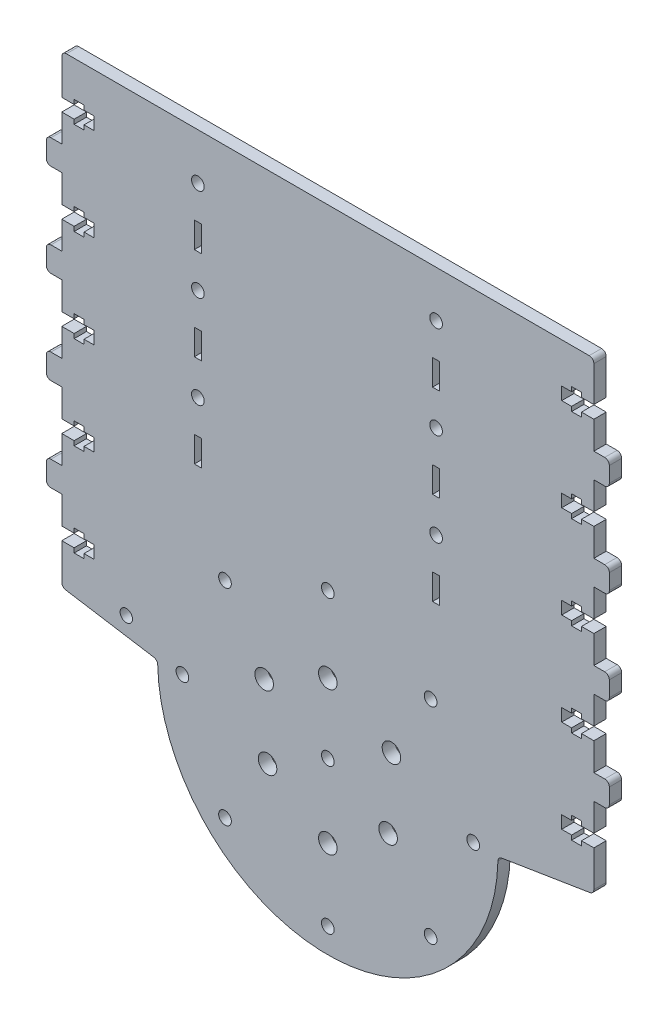
SolidWorks part; units mm, degrees
ref_plane "前视基准面" through (0, 0, 0) normal (0, 0, 1) x (1, 0, 0)
ref_plane "上视基准面" through (0, 0, 0) normal (0, 1, 0) x (1, 0, 0)
ref_plane "右视基准面" through (0, 0, 0) normal (1, 0, 0) x (0, 0, -1)
sketch "草图1" plane through (0, 0, 0) normal (0, 0, 1) x (1, 0, 0)
  line L9 (143, 45.95) -> (147, 45.95)
  line L10 (147, 45.95) -> (147, 44.5)
  line L11 (147, 44.5) -> (150.2, 44.5)
  line L12 (150.2, 44.5) -> (150.2, 45.95)
  line L13 (150.2, 45.95) -> (153.4, 45.95)
  line L14 (153.4, 45.95) -> (153.4, 50.05)
  line L23 (143, 48) -> (141.6922, 48) construction
  line L24 (143, 45.95) -> (143, 50.05) construction
  line L25 (150.2, 51.5) -> (150.2, 50.05)
  line L26 (147, 50.05) -> (147, 51.5)
  line L27 (150.2, 50.05) -> (153.4, 50.05)
  line L28 (147, 51.5) -> (150.2, 51.5)
  line L29 (143, 50.05) -> (147, 50.05)
  line L31 (143, 29) -> (138, 29)
  line L32 (138, 29) -> (138, 37)
  line L33 (138, 37) -> (143, 37)
  line L34 (143, 37) -> (143, 45.95)
  line L35 (138, 33) -> (143, 33) construction
  line L43 (143, 119) -> (143, 123)
  line L44 (229, -79) -> (229, -87) construction
  line L45 (143, 20.05) -> (143, 15.95) construction
  line L69 (143, -97) -> (311, -97) construction
  line L70 (143, 18) -> (141.6922, 18) construction
  line L71 (143, 15.95) -> (147, 15.95)
  line L72 (147, 15.95) -> (147, 14.5)
  line L73 (147, 14.5) -> (150.2, 14.5)
  line L98 (150.2, 14.5) -> (150.2, 15.95)
  line L123 (150.2, 15.95) -> (153.4, 15.95)
  line L124 (150.2, 21.5) -> (150.2, 20.05)
  line L125 (147, 20.05) -> (147, 21.5)
  line L126 (150.2, 20.05) -> (153.4, 20.05)
  line L127 (147, 21.5) -> (150.2, 21.5)
  line L128 (143, 20.05) -> (147, 20.05)
  line L129 (143, 7) -> (143, 15.95)
  line L130 (143, 15.95) -> (147, 15.95)
  line L131 (147, 14.5) -> (150.2, 14.5)
  line L132 (143, 15.95) -> (147, 15.95)
  line L133 (147, 15.95) -> (147, 14.5)
  line L134 (147, 14.5) -> (150.2, 14.5)
  line L135 (150.2, 14.5) -> (150.2, 15.95)
  line L136 (150.2, 15.95) -> (153.4, 15.95)
  line L137 (150.2, 21.5) -> (150.2, 20.05)
  line L138 (147, 20.05) -> (147, 21.5)
  line L139 (150.2, 20.05) -> (153.4, 20.05)
  line L140 (147, 21.5) -> (150.2, 21.5)
  line L141 (143, 20.05) -> (147, 20.05)
  line L142 (150.2, 15.95) -> (153.4, 15.95)
  line L143 (147, 15.95) -> (147, 14.5)
  line L144 (150.2, 14.5) -> (150.2, 15.95)
  line L145 (150.2, 20.05) -> (153.4, 20.05)
  line L146 (150.2, 21.5) -> (150.2, 20.05)
  line L147 (147, 21.5) -> (150.2, 21.5)
  line L148 (147, 20.05) -> (147, 21.5)
  line L149 (143, 20.05) -> (147, 20.05)
  line L150 (143, 45.95) -> (147, 45.95)
  line L151 (147, 45.95) -> (147, 44.5)
  line L152 (147, 44.5) -> (150.2, 44.5)
  line L153 (150.2, 44.5) -> (150.2, 45.95)
  line L154 (150.2, 45.95) -> (153.4, 45.95)
  line L155 (150.2, 51.5) -> (150.2, 50.05)
  line L156 (147, 50.05) -> (147, 51.5)
  line L157 (150.2, 50.05) -> (153.4, 50.05)
  line L158 (143, 45.95) -> (147, 45.95)
  line L159 (147, 44.5) -> (150.2, 44.5)
  line L160 (150.2, 45.95) -> (153.4, 45.95)
  line L161 (147, 45.95) -> (147, 44.5)
  line L162 (150.2, 44.5) -> (150.2, 45.95)
  line L163 (150.2, 50.05) -> (153.4, 50.05)
  line L164 (150.2, 51.5) -> (150.2, 50.05)
  line L165 (147, 51.5) -> (150.2, 51.5)
  line L166 (147, 50.05) -> (147, 51.5)
  line L167 (143, 50.05) -> (147, 50.05)
  line L168 (147, 51.5) -> (150.2, 51.5)
  line L169 (143, 50.05) -> (147, 50.05)
  line L170 (143, 29) -> (143, 20.05)
  line L171 (143, 15.95) -> (147, 15.95)
  line L172 (147, 14.5) -> (150.2, 14.5)
  line L173 (150.2, 15.95) -> (153.4, 15.95)
  line L174 (147, 15.95) -> (147, 14.5)
  line L175 (150.2, 14.5) -> (150.2, 15.95)
  line L177 (153.4, 20.05) -> (153.4, 15.95)
  line L178 (150.2, 20.05) -> (153.4, 20.05)
  line L179 (150.2, 21.5) -> (150.2, 20.05)
  line L180 (147, 21.5) -> (150.2, 21.5)
  line L181 (147, 20.05) -> (147, 21.5)
  line L182 (143, 20.05) -> (147, 20.05)
  line L183 (138, 3) -> (143, 3) construction
  line L184 (138, -1) -> (143, -1)
  line L185 (138, 7) -> (138, -1)
  line L186 (143, 7) -> (138, 7)
  line L187 (138, 93) -> (143, 93) construction
  line L188 (143, 78) -> (141.6922, 78) construction
  line L189 (272.15, 28.85) -> (269.85, 37.15) construction
  line L190 (138, 63) -> (143, 63) construction
  line L191 (143, 89) -> (138, 89)
  line L192 (138, 89) -> (138, 97)
  line L193 (138, 97) -> (143, 97)
  line L194 (143, 75.95) -> (147, 75.95)
  line L195 (147, 75.95) -> (147, 74.5)
  line L196 (147, 74.5) -> (150.2, 74.5)
  line L197 (150.2, 74.5) -> (150.2, 75.95)
  line L198 (150.2, 75.95) -> (153.4, 75.95)
  line L199 (143, 59) -> (143, 50.05)
  line L200 (138, 59) -> (143, 59)
  line L201 (153.4, 75.95) -> (153.4, 80.05)
  line L202 (150.2, 81.5) -> (150.2, 80.05)
  line L203 (143, 45.95) -> (147, 45.95)
  line L204 (147, 44.5) -> (150.2, 44.5)
  line L205 (150.2, 45.95) -> (153.4, 45.95)
  line L206 (147, 45.95) -> (147, 44.5)
  line L207 (150.2, 44.5) -> (150.2, 45.95)
  line L208 (150.2, 50.05) -> (153.4, 50.05)
  line L209 (150.2, 51.5) -> (150.2, 50.05)
  line L210 (147, 51.5) -> (150.2, 51.5)
  line L211 (147, 50.05) -> (147, 51.5)
  line L212 (143, 50.05) -> (147, 50.05)
  line L213 (272.15, 37.15) -> (269.85, 28.85) construction
  line L214 (147, 80.05) -> (147, 81.5)
  line L215 (150.2, 80.05) -> (153.4, 80.05)
  line L216 (147, 81.5) -> (150.2, 81.5)
  line L217 (143, 80.05) -> (147, 80.05)
  line L218 (143, 67) -> (143, 75.95)
  line L219 (143, 75.95) -> (147, 75.95)
  line L220 (147, 75.95) -> (147, 74.5)
  line L221 (147, 74.5) -> (150.2, 74.5)
  line L222 (150.2, 74.5) -> (150.2, 75.95)
  line L223 (150.2, 75.95) -> (153.4, 75.95)
  line L224 (150.2, 81.5) -> (150.2, 80.05)
  line L225 (147, 80.05) -> (147, 81.5)
  line L227 (271, 48) -> (271, 33) construction
  line L228 (272.15, 58.85) -> (269.85, 67.15) construction
  line L229 (272.15, 67.15) -> (269.85, 58.85) construction
  line L230 (150.2, 80.05) -> (153.4, 80.05)
  line L231 (143, 75.95) -> (147, 75.95)
  line L232 (147, 74.5) -> (150.2, 74.5)
  line L233 (150.2, 75.95) -> (153.4, 75.95)
  line L234 (147, 75.95) -> (147, 74.5)
  line L235 (150.2, 74.5) -> (150.2, 75.95)
  line L253 (150.2, 80.05) -> (153.4, 80.05)
  line L254 (150.2, 81.5) -> (150.2, 80.05)
  line L255 (143, -27) -> (143, -97) construction
  line L256 (147, 81.5) -> (150.2, 81.5)
  line L257 (147, 80.05) -> (147, 81.5)
  line L258 (143, 80.05) -> (147, 80.05)
  line L259 (147, 81.5) -> (150.2, 81.5)
  line L260 (143, 80.05) -> (147, 80.05)
  line L261 (143, 89) -> (143, 80.05)
  line L262 (143, 75.95) -> (147, 75.95)
  line L263 (147, 74.5) -> (150.2, 74.5)
  line L264 (150.2, 75.95) -> (153.4, 75.95)
  line L265 (147, 75.95) -> (147, 74.5)
  line L267 (150.2, 74.5) -> (150.2, 75.95)
  line L269 (150.2, 80.05) -> (153.4, 80.05)
  line L270 (150.2, 81.5) -> (150.2, 80.05)
  line L272 (147, 81.5) -> (150.2, 81.5)
  line L273 (147, 80.05) -> (147, 81.5)
  line L274 (143, 80.05) -> (147, 80.05)
  line L275 (138, 59) -> (143, 59)
  line L277 (138, 67) -> (138, 59)
  line L278 (143, 67) -> (138, 67)
  line L279 (143, 110.05) -> (143, 105.95) construction
  line L280 (143, 108) -> (141.6922, 108) construction
  line L281 (272.15, 88.85) -> (269.85, 97.15) construction
  line L282 (143, 105.95) -> (147, 105.95)
  line L283 (147, 105.95) -> (147, 104.5)
  line L284 (147, 104.5) -> (150.2, 104.5)
  line L285 (150.2, 104.5) -> (150.2, 105.95)
  line L286 (150.2, 105.95) -> (153.4, 105.95)
  line L287 (150.2, 111.5) -> (150.2, 110.05)
  line L288 (147, 110.05) -> (147, 111.5)
  line L289 (150.2, 110.05) -> (153.4, 110.05)
  line L290 (147, 111.5) -> (150.2, 111.5)
  line L291 (143, 110.05) -> (147, 110.05)
  line L292 (143, 97) -> (143, 105.95)
  line L293 (143, 105.95) -> (147, 105.95)
  line L294 (147, 104.5) -> (150.2, 104.5)
  line L296 (143, 105.95) -> (147, 105.95)
  line L300 (147, 105.95) -> (147, 104.5)
  line L301 (147, 104.5) -> (150.2, 104.5)
  line L302 (150.2, 104.5) -> (150.2, 105.95)
  line L303 (150.2, 105.95) -> (153.4, 105.95)
  line L304 (150.2, 111.5) -> (150.2, 110.05)
  line L305 (147, 110.05) -> (147, 111.5)
  line L306 (150.2, 110.05) -> (153.4, 110.05)
  line L307 (147, 111.5) -> (150.2, 111.5)
  line L308 (143, 110.05) -> (147, 110.05)
  line L309 (150.2, 105.95) -> (153.4, 105.95)
  line L310 (147, 105.95) -> (147, 104.5)
  line L312 (150.2, 104.5) -> (150.2, 105.95)
  line L314 (150.2, 110.05) -> (153.4, 110.05)
  line L315 (150.2, 111.5) -> (150.2, 110.05)
  line L317 (147, 111.5) -> (150.2, 111.5)
  line L320 (147, 110.05) -> (147, 111.5)
  line L321 (143, 110.05) -> (147, 110.05)
  line L322 (143, 119) -> (143, 110.05)
  line L323 (143, 105.95) -> (147, 105.95)
  line L324 (147, 104.5) -> (150.2, 104.5)
  line L325 (150.2, 105.95) -> (153.4, 105.95)
  line L326 (147, 105.95) -> (147, 104.5)
  line L327 (150.2, 104.5) -> (150.2, 105.95)
  line L328 (153.4, 110.05) -> (153.4, 105.95)
  line L329 (150.2, 110.05) -> (153.4, 110.05)
  line L330 (150.2, 111.5) -> (150.2, 110.05)
  line L331 (147, 111.5) -> (150.2, 111.5)
  line L332 (147, 110.05) -> (147, 111.5)
  line L333 (143, 110.05) -> (147, 110.05)
  line L334 (143, -14.05) -> (147, -14.05)
  line L335 (272.15, 97.15) -> (269.85, 88.85) construction
  line L336 (271, 108) -> (271, 48) construction
  line L337 (269.85, 37.15) -> (269.85, 28.85) construction
  line L338 (272.15, 28.85) -> (269.85, 28.85) construction
  line L339 (272.15, 37.15) -> (272.15, 28.85) construction
  line L340 (272.15, 37.15) -> (269.85, 37.15) construction
  line L341 (269.85, 67.15) -> (269.85, 58.85) construction
  line L342 (272.15, 58.85) -> (269.85, 58.85) construction
  line L343 (272.15, 67.15) -> (272.15, 58.85) construction
  line L344 (272.15, 67.15) -> (269.85, 67.15) construction
  line L345 (269.85, 97.15) -> (269.85, 88.85) construction
  line L346 (272.15, 88.85) -> (269.85, 88.85) construction
  line L347 (272.15, 97.15) -> (272.15, 88.85) construction
  line L348 (272.15, 97.15) -> (269.85, 97.15) construction
  line L349 (307.8, 110.05) -> (304.6, 110.05)
  line L350 (304.6, 110.05) -> (304.6, 105.95)
  line L352 (307.8, 105.95) -> (304.6, 105.95)
  line L353 (307.8, 110.05) -> (304.6, 110.05)
  line L355 (307.8, 105.95) -> (304.6, 105.95)
  line L357 (307.8, 110.05) -> (304.6, 110.05)
  line L358 (307.8, 105.95) -> (304.6, 105.95)
  line L359 (307.8, 110.05) -> (304.6, 110.05)
  line L360 (307.8, 105.95) -> (304.6, 105.95)
  line L361 (307.8, 80.05) -> (304.6, 80.05)
  line L362 (307.8, 75.95) -> (304.6, 75.95)
  line L363 (307.8, 80.05) -> (304.6, 80.05)
  line L364 (307.8, 75.95) -> (304.6, 75.95)
  line L365 (307.8, 80.05) -> (304.6, 80.05)
  line L367 (307.8, 75.95) -> (304.6, 75.95)
  line L369 (187, 108) -> (187, 48) construction
  line L370 (185.85, 97.15) -> (188.15, 97.15)
  line L371 (185.85, 97.15) -> (185.85, 88.85)
  line L372 (185.85, 88.85) -> (188.15, 88.85)
  line L373 (188.15, 97.15) -> (188.15, 88.85)
  line L374 (185.85, 97.15) -> (188.15, 88.85) construction
  line L375 (185.85, 88.85) -> (188.15, 97.15) construction
  line L387 (307.8, 80.05) -> (304.6, 80.05)
  line L389 (307.8, 50.05) -> (304.6, 50.05)
  line L391 (307.8, 45.95) -> (304.6, 45.95)
  line L392 (304.6, 75.95) -> (304.6, 80.05)
  line L420 (307.8, 75.95) -> (304.6, 75.95)
  line L421 (229, -32) -> (245.7973, -32) construction
  line L422 (229, -32) -> (253.7224, -46.2735) construction
  line L423 (185.85, 67.15) -> (188.15, 67.15)
  line L424 (185.85, 67.15) -> (185.85, 58.85)
  line L425 (185.85, 58.85) -> (188.15, 58.85)
  line L426 (188.15, 67.15) -> (188.15, 58.85)
  line L427 (185.85, 67.15) -> (188.15, 58.85) construction
  line L432 (185.85, 58.85) -> (188.15, 67.15) construction
  line L433 (307.8, 20.05) -> (304.6, 20.05)
  line L443 (187, 48) -> (187, 33) construction
  line L444 (304.6, 20.05) -> (304.6, 15.95)
  line L445 (185.85, 37.15) -> (188.15, 37.15)
  line L446 (185.85, 37.15) -> (185.85, 28.85)
  line L447 (185.85, 28.85) -> (188.15, 28.85)
  line L448 (188.15, 37.15) -> (188.15, 28.85)
  line L449 (185.85, 37.15) -> (188.15, 28.85) construction
  line L450 (185.85, 28.85) -> (188.15, 37.15) construction
  line L451 (307.8, 15.95) -> (304.6, 15.95)
  line L452 (307.8, 50.05) -> (304.6, 50.05)
  line L453 (307.8, 45.95) -> (304.6, 45.95)
  line L454 (307.8, 50.05) -> (304.6, 50.05)
  line L455 (307.8, 45.95) -> (304.6, 45.95)
  line L456 (307.8, 20.05) -> (304.6, 20.05)
  line L457 (307.8, 15.95) -> (304.6, 15.95)
  line L458 (307.8, 20.05) -> (304.6, 20.05)
  line L459 (307.8, 15.95) -> (304.6, 15.95)
  line L460 (307.8, 20.05) -> (304.6, 20.05)
  line L461 (307.8, 15.95) -> (304.6, 15.95)
  line L462 (307.8, 50.05) -> (304.6, 50.05)
  line L463 (304.6, 45.95) -> (304.6, 50.05)
  line L464 (307.8, 45.95) -> (304.6, 45.95)
  line L465 (315, 108) -> (316.3078, 108) construction
  line L466 (315, 110.05) -> (315, 105.95) construction
  line L467 (320, 63) -> (315, 63) construction
  line L468 (315, 78) -> (316.3078, 78) construction
  line L469 (320, 93) -> (315, 93) construction
  line L470 (320, 3) -> (315, 3) construction
  line L471 (315, 18) -> (316.3078, 18) construction
  line L472 (315, 20.05) -> (315, 15.95) construction
  line L473 (320, 33) -> (315, 33) construction
  line L474 (315, 45.95) -> (315, 50.05) construction
  line L475 (315, 48) -> (316.3078, 48) construction
  line L476 (315, -14.05) -> (315, -27)
  line L477 (315, 110.05) -> (311, 110.05)
  line L478 (311, 110.05) -> (311, 111.5)
  line L479 (311, 111.5) -> (307.8, 111.5)
  line L480 (307.8, 111.5) -> (307.8, 110.05)
  line L481 (307.8, 104.5) -> (307.8, 105.95)
  line L482 (311, 105.95) -> (311, 104.5)
  line L483 (311, 104.5) -> (307.8, 104.5)
  line L484 (315, 105.95) -> (311, 105.95)
  line L485 (315, 119) -> (315, 110.05)
  line L486 (315, 110.05) -> (311, 110.05)
  line L487 (311, 110.05) -> (311, 111.5)
  line L488 (311, 111.5) -> (307.8, 111.5)
  line L489 (307.8, 111.5) -> (307.8, 110.05)
  line L490 (307.8, 104.5) -> (307.8, 105.95)
  line L491 (311, 105.95) -> (311, 104.5)
  line L492 (315, 110.05) -> (311, 110.05)
  line L493 (311, 111.5) -> (307.8, 111.5)
  line L494 (311, 110.05) -> (311, 111.5)
  line L495 (307.8, 111.5) -> (307.8, 110.05)
  line L496 (307.8, 104.5) -> (307.8, 105.95)
  line L497 (311, 104.5) -> (307.8, 104.5)
  line L498 (311, 105.95) -> (311, 104.5)
  line L499 (315, 105.95) -> (311, 105.95)
  line L500 (311, 104.5) -> (307.8, 104.5)
  line L501 (315, 105.95) -> (311, 105.95)
  line L502 (315, 97) -> (315, 105.95)
  line L503 (315, 110.05) -> (311, 110.05)
  line L504 (311, 111.5) -> (307.8, 111.5)
  line L505 (311, 110.05) -> (311, 111.5)
  line L506 (307.8, 111.5) -> (307.8, 110.05)
  line L507 (307.8, 104.5) -> (307.8, 105.95)
  line L508 (311, 104.5) -> (307.8, 104.5)
  line L509 (311, 105.95) -> (311, 104.5)
  line L510 (315, 105.95) -> (311, 105.95)
  line L511 (315, 67) -> (320, 67)
  line L512 (320, 67) -> (320, 59)
  line L513 (320, 59) -> (315, 59)
  line L514 (315, 80.05) -> (311, 80.05)
  line L515 (311, 80.05) -> (311, 81.5)
  line L516 (311, 81.5) -> (307.8, 81.5)
  line L517 (307.8, 81.5) -> (307.8, 80.05)
  line L518 (307.8, 74.5) -> (307.8, 75.95)
  line L519 (311, 75.95) -> (311, 74.5)
  line L520 (311, 74.5) -> (307.8, 74.5)
  line L521 (315, 75.95) -> (311, 75.95)
  line L522 (315, 89) -> (315, 80.05)
  line L523 (315, 80.05) -> (311, 80.05)
  line L524 (311, 81.5) -> (307.8, 81.5)
  line L525 (315, 80.05) -> (311, 80.05)
  line L526 (311, 80.05) -> (311, 81.5)
  line L527 (311, 81.5) -> (307.8, 81.5)
  line L528 (307.8, 81.5) -> (307.8, 80.05)
  line L529 (307.8, 74.5) -> (307.8, 75.95)
  line L530 (311, 75.95) -> (311, 74.5)
  line L531 (311, 74.5) -> (307.8, 74.5)
  line L532 (315, 75.95) -> (311, 75.95)
  line L533 (311, 80.05) -> (311, 81.5)
  line L534 (307.8, 81.5) -> (307.8, 80.05)
  line L535 (307.8, 74.5) -> (307.8, 75.95)
  line L536 (311, 74.5) -> (307.8, 74.5)
  line L537 (311, 75.95) -> (311, 74.5)
  line L538 (315, 75.95) -> (311, 75.95)
  line L539 (315, 67) -> (315, 75.95)
  line L540 (315, 80.05) -> (311, 80.05)
  line L541 (311, 81.5) -> (307.8, 81.5)
  line L542 (311, 80.05) -> (311, 81.5)
  line L543 (315, 50.05) -> (311, 50.05)
  line L544 (311, 50.05) -> (311, 51.5)
  line L545 (311, 51.5) -> (307.8, 51.5)
  line L546 (307.8, 51.5) -> (307.8, 50.05)
  line L547 (307.8, 44.5) -> (307.8, 45.95)
  line L548 (311, 45.95) -> (311, 44.5)
  line L549 (311, 44.5) -> (307.8, 44.5)
  line L550 (315, 45.95) -> (311, 45.95)
  line L551 (307.8, 81.5) -> (307.8, 80.05)
  line L552 (320, 59) -> (315, 59)
  line L553 (315, 59) -> (315, 50.05)
  line L554 (307.8, 74.5) -> (307.8, 75.95)
  line L555 (311, 74.5) -> (307.8, 74.5)
  line L556 (311, 75.95) -> (311, 74.5)
  line L557 (315, 75.95) -> (311, 75.95)
  line L558 (320, 97) -> (315, 97)
  line L559 (320, 89) -> (320, 97)
  line L560 (315, 89) -> (320, 89)
  line L561 (315, 7) -> (320, 7)
  line L562 (320, 7) -> (320, -1)
  line L563 (320, -1) -> (315, -1)
  line L564 (315, 20.05) -> (311, 20.05)
  line L565 (311, 20.05) -> (311, 21.5)
  line L566 (311, 21.5) -> (307.8, 21.5)
  line L567 (307.8, 21.5) -> (307.8, 20.05)
  line L568 (307.8, 14.5) -> (307.8, 15.95)
  line L569 (311, 15.95) -> (311, 14.5)
  line L570 (311, 14.5) -> (307.8, 14.5)
  line L571 (315, 15.95) -> (311, 15.95)
  line L572 (315, 29) -> (315, 20.05)
  line L573 (315, 50.05) -> (311, 50.05)
  line L574 (311, 51.5) -> (307.8, 51.5)
  line L575 (315, 50.05) -> (311, 50.05)
  line L576 (311, 50.05) -> (311, 51.5)
  line L577 (311, 51.5) -> (307.8, 51.5)
  line L578 (307.8, 51.5) -> (307.8, 50.05)
  line L579 (307.8, 44.5) -> (307.8, 45.95)
  line L580 (311, 45.95) -> (311, 44.5)
  line L581 (311, 44.5) -> (307.8, 44.5)
  line L582 (315, 45.95) -> (311, 45.95)
  line L583 (311, 50.05) -> (311, 51.5)
  line L584 (307.8, 51.5) -> (307.8, 50.05)
  line L585 (307.8, 44.5) -> (307.8, 45.95)
  line L586 (311, 44.5) -> (307.8, 44.5)
  line L587 (311, 45.95) -> (311, 44.5)
  line L588 (315, 45.95) -> (311, 45.95)
  line L589 (315, 20.05) -> (311, 20.05)
  line L590 (311, 20.05) -> (311, 21.5)
  line L591 (311, 21.5) -> (307.8, 21.5)
  line L592 (307.8, 21.5) -> (307.8, 20.05)
  line L593 (307.8, 14.5) -> (307.8, 15.95)
  line L594 (311, 15.95) -> (311, 14.5)
  line L595 (315, 20.05) -> (311, 20.05)
  line L596 (311, 21.5) -> (307.8, 21.5)
  line L597 (311, 20.05) -> (311, 21.5)
  line L598 (307.8, 21.5) -> (307.8, 20.05)
  line L599 (307.8, 14.5) -> (307.8, 15.95)
  line L600 (311, 14.5) -> (307.8, 14.5)
  line L601 (311, 15.95) -> (311, 14.5)
  line L602 (315, 15.95) -> (311, 15.95)
  line L603 (311, 14.5) -> (307.8, 14.5)
  line L604 (315, 15.95) -> (311, 15.95)
  line L605 (315, 7) -> (315, 15.95)
  line L606 (315, 20.05) -> (311, 20.05)
  line L607 (311, 21.5) -> (307.8, 21.5)
  line L608 (311, 20.05) -> (311, 21.5)
  line L609 (307.8, 21.5) -> (307.8, 20.05)
  line L610 (307.8, 14.5) -> (307.8, 15.95)
  line L611 (311, 14.5) -> (307.8, 14.5)
  line L612 (311, 15.95) -> (311, 14.5)
  line L613 (315, 15.95) -> (311, 15.95)
  line L614 (315, 119) -> (315, 123)
  line L615 (315, 37) -> (315, 45.95)
  line L616 (320, 37) -> (315, 37)
  line L617 (320, 29) -> (320, 37)
  line L618 (315, 29) -> (320, 29)
  line L619 (315, 50.05) -> (311, 50.05)
  line L620 (311, 51.5) -> (307.8, 51.5)
  line L621 (311, 50.05) -> (311, 51.5)
  line L622 (307.8, 51.5) -> (307.8, 50.05)
  line L623 (307.8, 44.5) -> (307.8, 45.95)
  line L624 (311, 44.5) -> (307.8, 44.5)
  line L625 (311, 45.95) -> (311, 44.5)
  line L626 (315, 45.95) -> (311, 45.95)
  line L627 (315, 123) -> (143, 123)
  line L628 (143, -27) -> (174, -32)
  line L629 (284, -32) -> (315, -27)
  line L630 (147, -14.05) -> (147, -15.5)
  line L631 (147, -15.5) -> (150.2, -15.5)
  line L632 (150.2, -15.5) -> (150.2, -14.05)
  line L633 (150.2, -14.05) -> (153.4, -14.05)
  line L634 (153.4, -14.05) -> (153.4, -9.95)
  line L635 (150.2, -8.5) -> (150.2, -9.95)
  line L636 (147, -9.95) -> (147, -8.5)
  line L637 (150.2, -9.95) -> (153.4, -9.95)
  line L638 (147, -8.5) -> (150.2, -8.5)
  line L639 (143, -9.95) -> (147, -9.95)
  line L640 (143, -14.05) -> (147, -14.05)
  line L641 (147, -14.05) -> (147, -15.5)
  line L642 (147, -15.5) -> (150.2, -15.5)
  line L643 (150.2, -15.5) -> (150.2, -14.05)
  line L644 (150.2, -14.05) -> (153.4, -14.05)
  line L645 (150.2, -8.5) -> (150.2, -9.95)
  line L646 (147, -9.95) -> (147, -8.5)
  line L647 (150.2, -9.95) -> (153.4, -9.95)
  line L648 (143, -14.05) -> (147, -14.05)
  line L649 (147, -15.5) -> (150.2, -15.5)
  line L650 (150.2, -14.05) -> (153.4, -14.05)
  line L651 (147, -14.05) -> (147, -15.5)
  line L652 (150.2, -15.5) -> (150.2, -14.05)
  line L653 (150.2, -9.95) -> (153.4, -9.95)
  line L654 (150.2, -8.5) -> (150.2, -9.95)
  line L655 (147, -8.5) -> (150.2, -8.5)
  line L656 (147, -9.95) -> (147, -8.5)
  line L657 (143, -9.95) -> (147, -9.95)
  line L658 (147, -8.5) -> (150.2, -8.5)
  line L659 (143, -9.95) -> (147, -9.95)
  line L660 (143, -14.05) -> (147, -14.05)
  line L661 (147, -15.5) -> (150.2, -15.5)
  line L662 (150.2, -14.05) -> (153.4, -14.05)
  line L663 (147, -14.05) -> (147, -15.5)
  line L664 (150.2, -15.5) -> (150.2, -14.05)
  line L665 (150.2, -9.95) -> (153.4, -9.95)
  line L666 (150.2, -8.5) -> (150.2, -9.95)
  line L667 (147, -8.5) -> (150.2, -8.5)
  line L668 (147, -9.95) -> (147, -8.5)
  line L669 (143, -9.95) -> (147, -9.95)
  line L670 (143, -9.95) -> (143, -1)
  line L671 (143, -14.05) -> (143, -27)
  line L672 (315, -9.95) -> (315, -1)
  line L673 (315, -9.95) -> (311, -9.95)
  line L674 (311, -9.95) -> (311, -8.5)
  line L675 (311, -8.5) -> (307.8, -8.5)
  line L676 (307.8, -8.5) -> (307.8, -9.95)
  line L677 (307.8, -9.95) -> (304.6, -9.95)
  line L678 (307.8, -15.5) -> (307.8, -14.05)
  line L679 (311, -14.05) -> (311, -15.5)
  line L680 (307.8, -14.05) -> (304.6, -14.05)
  line L681 (311, -15.5) -> (307.8, -15.5)
  line L682 (315, -14.05) -> (311, -14.05)
  line L683 (315, -9.95) -> (311, -9.95)
  line L684 (311, -8.5) -> (307.8, -8.5)
  line L685 (315, -9.95) -> (311, -9.95)
  line L686 (311, -9.95) -> (311, -8.5)
  line L687 (311, -8.5) -> (307.8, -8.5)
  line L688 (307.8, -8.5) -> (307.8, -9.95)
  line L689 (307.8, -9.95) -> (304.6, -9.95)
  line L690 (307.8, -15.5) -> (307.8, -14.05)
  line L691 (311, -14.05) -> (311, -15.5)
  line L692 (307.8, -14.05) -> (304.6, -14.05)
  line L693 (311, -15.5) -> (307.8, -15.5)
  line L694 (315, -14.05) -> (311, -14.05)
  line L695 (307.8, -9.95) -> (304.6, -9.95)
  line L696 (311, -9.95) -> (311, -8.5)
  line L697 (307.8, -8.5) -> (307.8, -9.95)
  line L698 (307.8, -14.05) -> (304.6, -14.05)
  line L699 (307.8, -15.5) -> (307.8, -14.05)
  line L700 (311, -15.5) -> (307.8, -15.5)
  line L701 (311, -14.05) -> (311, -15.5)
  line L702 (315, -14.05) -> (311, -14.05)
  line L703 (315, -9.95) -> (311, -9.95)
  line L704 (311, -8.5) -> (307.8, -8.5)
  line L705 (307.8, -9.95) -> (304.6, -9.95)
  line L706 (311, -9.95) -> (311, -8.5)
  line L707 (307.8, -8.5) -> (307.8, -9.95)
  line L708 (304.6, -14.05) -> (304.6, -9.95)
  line L709 (307.8, -14.05) -> (304.6, -14.05)
  line L710 (307.8, -15.5) -> (307.8, -14.05)
  line L711 (311, -15.5) -> (307.8, -15.5)
  line L712 (311, -14.05) -> (311, -15.5)
  line L713 (315, -14.05) -> (311, -14.05)
  line L714 (264, 108) -> (264, 48) construction
  line L715 (262.85, 97.15) -> (265.15, 97.15)
  line L716 (262.85, 97.15) -> (262.85, 88.85)
  line L717 (262.85, 88.85) -> (265.15, 88.85)
  line L718 (265.15, 97.15) -> (265.15, 88.85)
  line L719 (262.85, 97.15) -> (265.15, 88.85) construction
  line L720 (262.85, 88.85) -> (265.15, 97.15) construction
  line L721 (262.85, 67.15) -> (265.15, 67.15)
  line L734 (271, 108) -> (264, 108) construction
  line L735 (262.85, 67.15) -> (262.85, 58.85)
  line L736 (262.85, 58.85) -> (265.15, 58.85)
  line L737 (265.15, 67.15) -> (265.15, 58.85)
  line L738 (262.85, 67.15) -> (265.15, 58.85) construction
  line L739 (262.85, 58.85) -> (265.15, 67.15) construction
  line L740 (264, 48) -> (264, 33) construction
  line L741 (262.85, 37.15) -> (265.15, 37.15)
  line L742 (262.85, 37.15) -> (262.85, 28.85)
  line L743 (262.85, 28.85) -> (265.15, 28.85)
  line L744 (265.15, 37.15) -> (265.15, 28.85)
  line L745 (262.85, 37.15) -> (265.15, 28.85) construction
  line L746 (262.85, 28.85) -> (265.15, 37.15) construction
  circle A88 centre (187, 108) radius 2.05
  circle A97 centre (229, -32) radius 23.75 construction
  circle A98 centre (229, -32) radius 22.5 construction
  circle A99 centre (229, -55.75) radius 3
  circle A100 centre (248.4856, -43.25) radius 3
  circle A101 centre (229, -32) radius 2.05
  circle A102 centre (276, -32) radius 2.05
  circle A103 centre (208.4319, -20.125) radius 3
  circle A104 centre (249.5681, -20.125) radius 3
  circle A105 centre (209.5144, -43.25) radius 3
  circle A106 centre (229, -9.5) radius 3
  circle A114 centre (187, 78) radius 2.05
  circle A115 centre (187, 48) radius 2.05
  circle A119 centre (262.234, -65.234) radius 2.05
  circle A120 centre (229, -79) radius 2.05
  circle A121 centre (195.766, -65.234) radius 2.05
  circle A122 centre (182, -32) radius 2.05
  circle A123 centre (195.766, 1.234) radius 2.05
  circle A124 centre (229, 15) radius 2.05
  circle A125 centre (262.234, 1.234) radius 2.05
  circle A126 centre (229, -32) radius 55 construction
  arc A127 (174, -32) -> (284, -32) centre (229, -32) ccw
  circle A128 centre (271, 48) radius 2.05 construction
  circle A129 centre (271, 78) radius 2.05 construction
  circle A130 centre (271, 108) radius 2.05 construction
  circle A131 centre (163.8583, -24.5718) radius 2
  circle A132 centre (264, 108) radius 2.05
  circle A133 centre (264, 78) radius 2.05
  circle A134 centre (264, 48) radius 2.05
  point P15 (142.3461, 48)
  point P103 (271, 63)
  point P104 (271, 93)
  point P199 (187, 93)
  point P208 (187, 63)
  point P238 (264, 93)
  point P284 (264, 63)
  dimension "D7" = 8
  dimension "D9" = 4.1
  dimension "D10" = 2.3
  dimension "D11" = 2.3
  dimension "D13" = 15
  dimension "D14" = 8.3
  dimension "D15" = 47.5
  dimension "D16" = 45
  dimension "D17" = 6
  dimension "D19" = 6
  dimension "D21" = 4.1
  dimension "D22" = 4.1
  dimension "D25" = 30
  dimension "D26" = 15
  dimension "D27" = 4.1
  dimension "D3" = 4
  dimension "D4" = 172
  dimension "D5" = 3.2
  dimension "D6" = 7
  dimension "D8" = 2.05
  dimension "D12" = 8.3
  dimension "D18" = 30
  dimension "D20" = 47
  dimension "D23" = 15
  dimension "D28" = 15
  dimension "D24" = 8
extrude "凸台-拉伸1" add sketch "草图1" along normal blind 4
sketch "草图2" plane through (143, 0, 0) normal (-1, 0, 0) x (0, 0, 1)
  line L0 (2, 20.05) -> (2, 15.95)
  line L1 (4, 20.05) -> (0, 20.05) construction
  line L2 (4, 15.95) -> (0, 15.95) construction
  circle A0 centre (2, 18) radius 2.05
sketch "草图3" plane through (315, 0, 0) normal (1, 0, 0) x (0, 0, -1)
  line L0 (-2, 15.95) -> (-2, 20.05)
  line L1 (-4, 15.95) -> (0, 15.95) construction
  line L2 (-4, 20.05) -> (0, 20.05) construction
  circle A0 centre (-2, 18) radius 2.05
fillet "圆角1" radius 1.5 22 edges at (284, -32, 2) (174, -32, 2) (315, 123, 2) (143, 123, 2) (138, 97, 2) (138, 67, 2) (138, 37, 2) (138, 29, 2) (138, 59, 2) (138, 89, 2) (138, 7, 2) (138, -1, 2) (143, -27, 2) (315, -27, 2) (320, 89, 2) (320, 97, 2) (320, 67, 2) (320, 59, 2) (320, 37, 2) (320, 29, 2) (320, 7, 2) (320, -1, 2)
